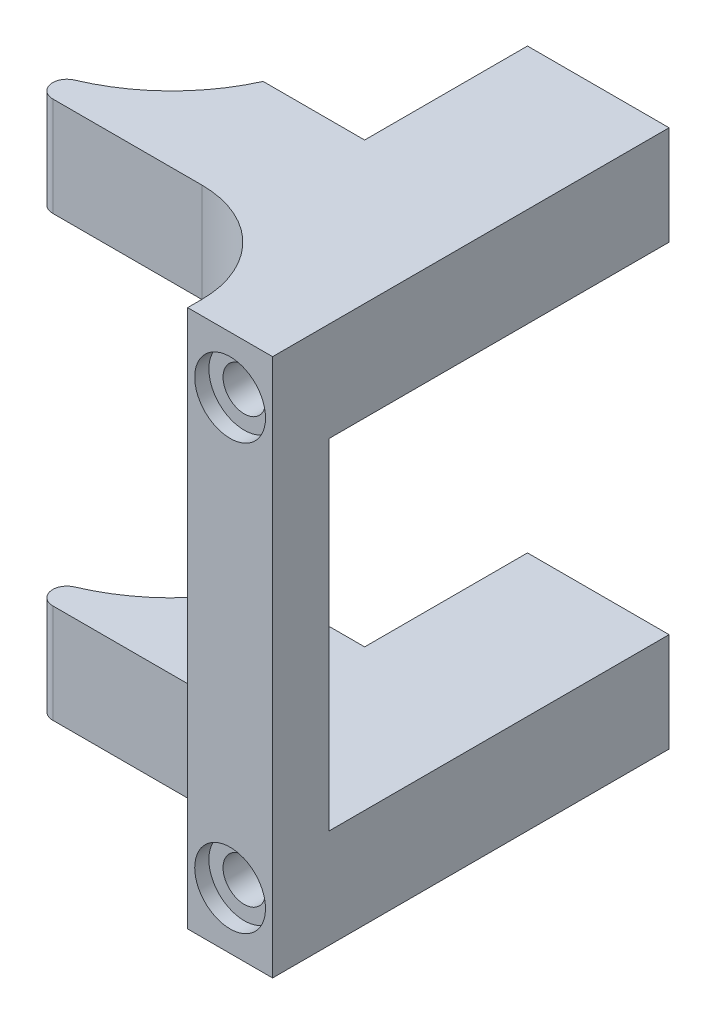
SolidWorks part; units mm, degrees
material "PLA"
ref_plane "前视基准面" through (0, 0, 0) normal (0, 0, 1) x (1, 0, 0)
ref_plane "上视基准面" through (0, 0, 0) normal (0, 1, 0) x (1, 0, 0)
ref_plane "右视基准面" through (0, 0, 0) normal (1, 0, 0) x (0, 0, -1)
sketch "草图1" plane through (0, 0, 0) normal (0, 1, 0) x (1, 0, 0)
  line L1 (-5, -10) -> (5, -10)
  line L2 (-5, -10) -> (-5, 10)
  line L3 (-5, 10) -> (5, 10)
  line L4 (5, -10) -> (5, 10)
  line L5 (0, 10) -> (0, -10) construction
  line L6 (-5, 0) -> (5, 0) construction
  point P0 (0, 0)
  dimension "D1" = 10
  dimension "D2" = 20
extrude "凸台-拉伸1" add sketch "草图1" along normal blind 38
sketch "草图3" plane through (0, 0, 0) normal (0, -1, 0) x (1, 0, 0)
  line L1 (5, -10) -> (-5, -10) construction
  line L9 (-18.5239, 10) -> (-5, 10)
  line L10 (-5, 10) -> (-5, 1.5)
  line L11 (-5, -10) -> (-5, 10) construction
  line L12 (-5, 1.5) -> (-12.1671, 1.5)
  arc A2 (-18.5239, 10) -> (-18.915, 8.0797) centre (-18.5239, 9) ccw
  arc A5 (-12.1671, 1.5) -> (-18.915, 8.0797) centre (-23.9994, -3.8848) ccw
  dimension "D3" = 1
  dimension "D4" = 18.9994
  dimension "D1" = 6.1152
  dimension "D6" = 26
  dimension "D2" = 8.5
extrude "凸台-拉伸5" add sketch "草图3" against normal up to surface (38 mm away) up to face at (0, 38, 0)
sketch "草图2" plane through (0, 0, 10) normal (0, 0, 1) x (1, 0, 0)
  line L0 (2, 0) -> (2, 38) construction
  line L1 (5, 38) -> (5, 0) construction
  line L3 (-18.5239, 38) -> (5, 38) construction
  line L4 (5, 19) -> (-18.5239, 19) construction
  line L5 (-18.5239, 38) -> (-18.5239, 0) construction
  circle A0 centre (2, 4) radius 1.5
  circle A1 centre (2, 34) radius 1.5
  dimension "D1" = 3
  dimension "D2" = 30
  dimension "D3" = 3
extrude "切除-拉伸1" cut sketch "草图2" against normal through all
sketch "草图10" plane through (5, 0, 0) normal (1, 0, 0) x (0, 0, -1)
  line L0 (-10, 38) -> (-10, 0) construction
  line L1 (-10, 7) -> (10, 7)
  line L2 (-10, 7) -> (-10, 31)
  line L3 (-10, 31) -> (10, 31)
  line L4 (10, 7) -> (10, 31)
  line L5 (0, 31) -> (0, 7) construction
  line L6 (-10, 19) -> (10, 19) construction
  line L7 (10, 38) -> (10, 0) construction
  line L8 (-10, 38) -> (10, 38) construction
  point P196 (0, 19)
  dimension "D1" = 7
extrude "切除-拉伸3" cut sketch "草图10" against normal through all
sketch "草图11" plane through (0, 0, 10) normal (0, 0, 1) x (1, 0, 0)
  line L0 (-18.5239, 7) -> (5, 7) construction
  line L1 (5, 0) -> (-1, 0)
  line L2 (5, 0) -> (5, 7)
  line L3 (5, 7) -> (-1, 7)
  line L4 (-1, 0) -> (-1, 7)
  line L5 (-19.5239, 7) -> (-19.5239, 31) construction
  line L6 (-19.5239, 19) -> (5, 19) construction
  line L7 (5, 38) -> (5, 31) construction
  line L8 (-1, 38) -> (-1, 31)
  line L9 (5, 31) -> (-1, 31)
  line L10 (5, 38) -> (5, 31)
  line L11 (5, 38) -> (-1, 38)
  circle A0 centre (2, 4) radius 1.5 construction
  circle A1 centre (2, 4) radius 1.5
  circle A2 centre (2, 34) radius 1.5
  dimension "D1" = 6
extrude "凸台-拉伸6" add sketch "草图11" along normal blind 8
sketch "草图12" plane through (0, 31, 0) normal (0, -1, 0) x (1, 0, 0)
  line L0 (5, 18) -> (5, -10) construction
  line L1 (-1, 18) -> (5, 18)
  line L2 (-1, 18) -> (-1, 14)
  line L3 (-1, 14) -> (5, 14)
  line L4 (5, 18) -> (5, 14)
  dimension "D1" = 4
extrude "凸台-拉伸7" add sketch "草图12" along normal up to surface (24 mm away) up to face at (-5.7526, 7, 5.3192)
fillet "圆角1" radius 7 1 edges at (-1, 3.5, 10)
sketch "草图13" plane through (0, 0, 18) normal (0, 0, 1) x (1, 0, 0)
  line L0 (5, 19) -> (-1, 19) construction
  line L1 (5, 0) -> (5, 38) construction
  line L2 (-1, 38) -> (-1, 0) construction
  circle A0 centre (2, 34) radius 2.5
  circle A1 centre (2, 4) radius 2.5
  dimension "D1" = 5
extrude "切除-拉伸4" cut sketch "草图13" against normal blind 1
move or copy body "实体-移动/复制1" [suppressed] bodies to move or copy 125
